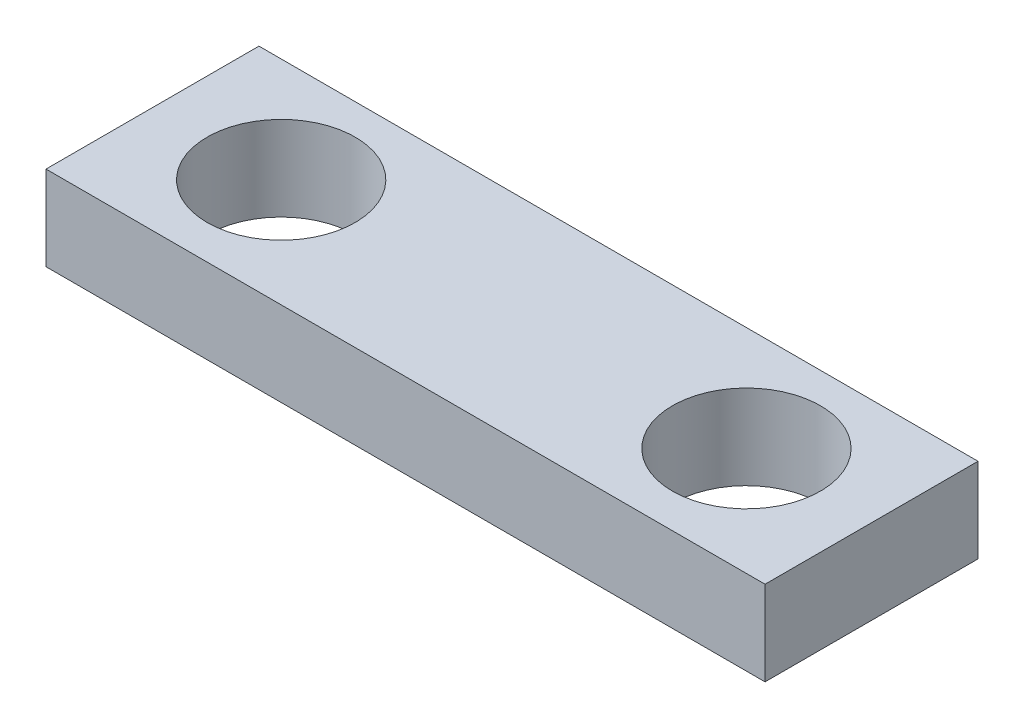
SolidWorks part; units mm, degrees
ref_plane "前视基准面" through (0, 0, 0) normal (0, 0, 1) x (1, 0, 0)
ref_plane "上视基准面" through (0, 0, 0) normal (0, 1, 0) x (1, 0, 0)
ref_plane "右视基准面" through (0, 0, 0) normal (1, 0, 0) x (0, 0, -1)
other "Configuration Table"
sketch "草图1" plane through (0, 0, 0) normal (0, 1, 0) x (1, 0, 0)
  line L1 (-8.6188, 2.8587) -> (8.3812, 2.8587)
  line L2 (-8.6188, 2.8587) -> (-8.6188, -2.176)
  line L3 (-8.6188, -2.176) -> (8.3812, -2.176)
  line L4 (8.3812, 2.8587) -> (8.3812, -2.176)
  circle A0 centre (-5.6188, 0.384) radius 1.75
  circle A1 centre (5.3812, 0.384) radius 1.75
  dimension "D1" = 3.5
  dimension "D2" = 3.5
  dimension "D3" = 3
  dimension "D4" = 3
  dimension "D5" = 11
extrude "凸台-拉伸1" add sketch "草图1" along normal blind 2
